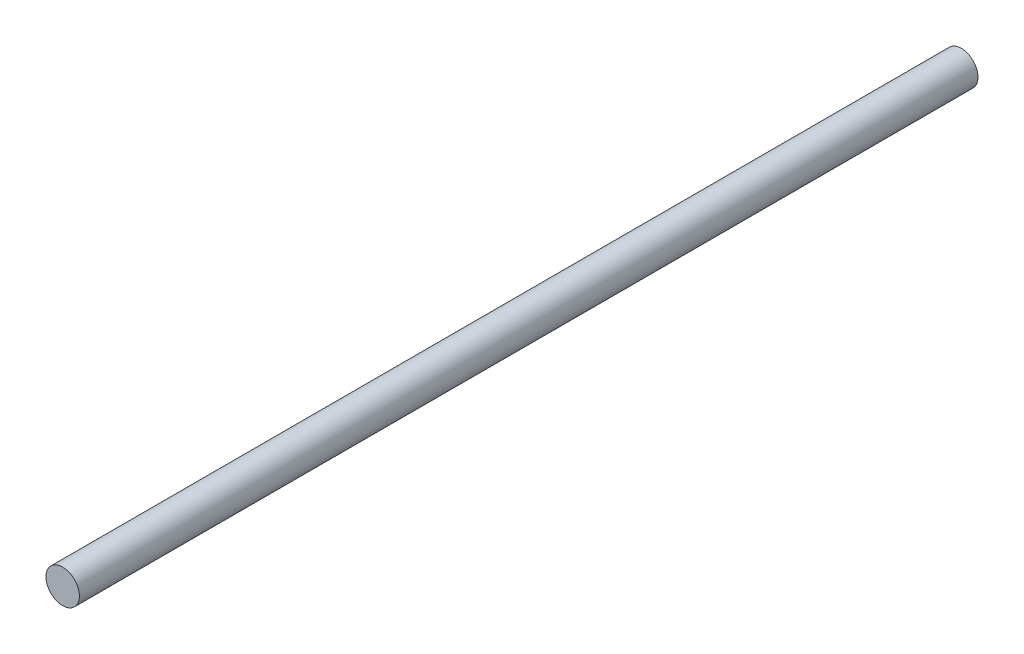
SolidWorks part; units mm, degrees
ref_plane "前视基准面" through (0, 0, 0) normal (0, 0, 1) x (1, 0, 0)
ref_plane "上视基准面" through (0, 0, 0) normal (0, 1, 0) x (1, 0, 0)
ref_plane "右视基准面" through (0, 0, 0) normal (1, 0, 0) x (0, 0, -1)
sketch "草图1" plane through (0, 0, 0) normal (0, 0, 1) x (1, 0, 0)
  circle A0 centre (0, 0) radius 4
  dimension "D1" = 8
extrude "凸台-拉伸1" add sketch "草图1" along normal blind 215
